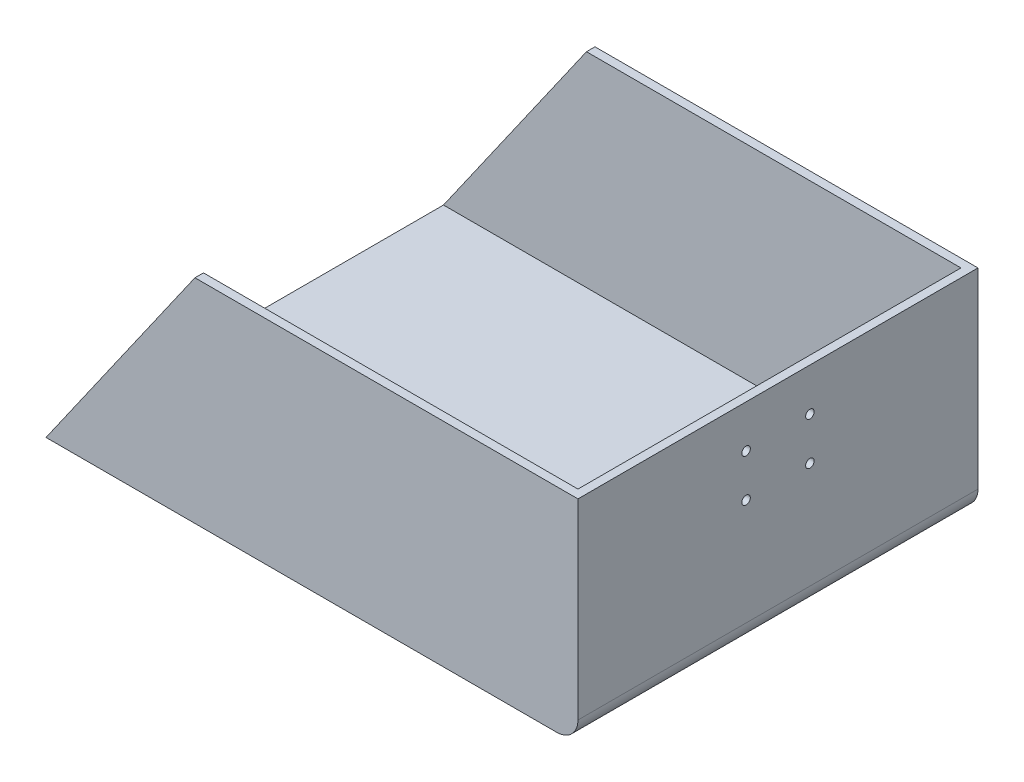
SolidWorks part; units mm, degrees
ref_plane "Płaszczyzna przednia" through (0, 0, 0) normal (0, 0, 1) x (1, 0, 0)
ref_plane "Płaszczyzna górna" through (0, 0, 0) normal (0, 1, 0) x (1, 0, 0)
ref_plane "Płaszczyzna prawa" through (0, 0, 0) normal (1, 0, 0) x (0, 0, -1)
sketch "Szkic1" plane through (0, 0, 0) normal (0, 0, 1) x (1, 0, 0)
  line L0 (-10, 0) -> (-250, 0)
  line L1 (0, 10) -> (0, 100)
  line L3 (0, 100) -> (-180, 100)
  line L4 (-180, 100) -> (-250, 0)
  arc A0 (0, 10) -> (-10, 0) centre (-10, 10) cw
  point P6 (0, 0)
  dimension "D3" = 10
  dimension "D1" = 250
  dimension "D2" = 100
  dimension "D4" = 180
extrude "Dodanie-wyciągnięcie1" add sketch "Szkic1" along normal blind 188
shell "Skorupa1" thickness 4
sketch "Szkic2" plane through (0, 0, 0) normal (1, 0, 0) x (0, 0, -1)
  line L0 (-94, 100) -> (-94, -10.5686) construction
  line L1 (-188, 100) -> (0, 100) construction
  circle A0 centre (-109, 80) radius 2
  circle A1 centre (-79, 80) radius 2
  circle A2 centre (-79, 60) radius 2
  circle A3 centre (-109, 60) radius 2
  dimension "D1" = 4
  dimension "D3" = 20
  dimension "D2" = 15
  dimension "D4" = 2
  dimension "D5" = 2
extrude "Wytnij-wyciągnięcie1" cut sketch "Szkic2" against normal blind 120
